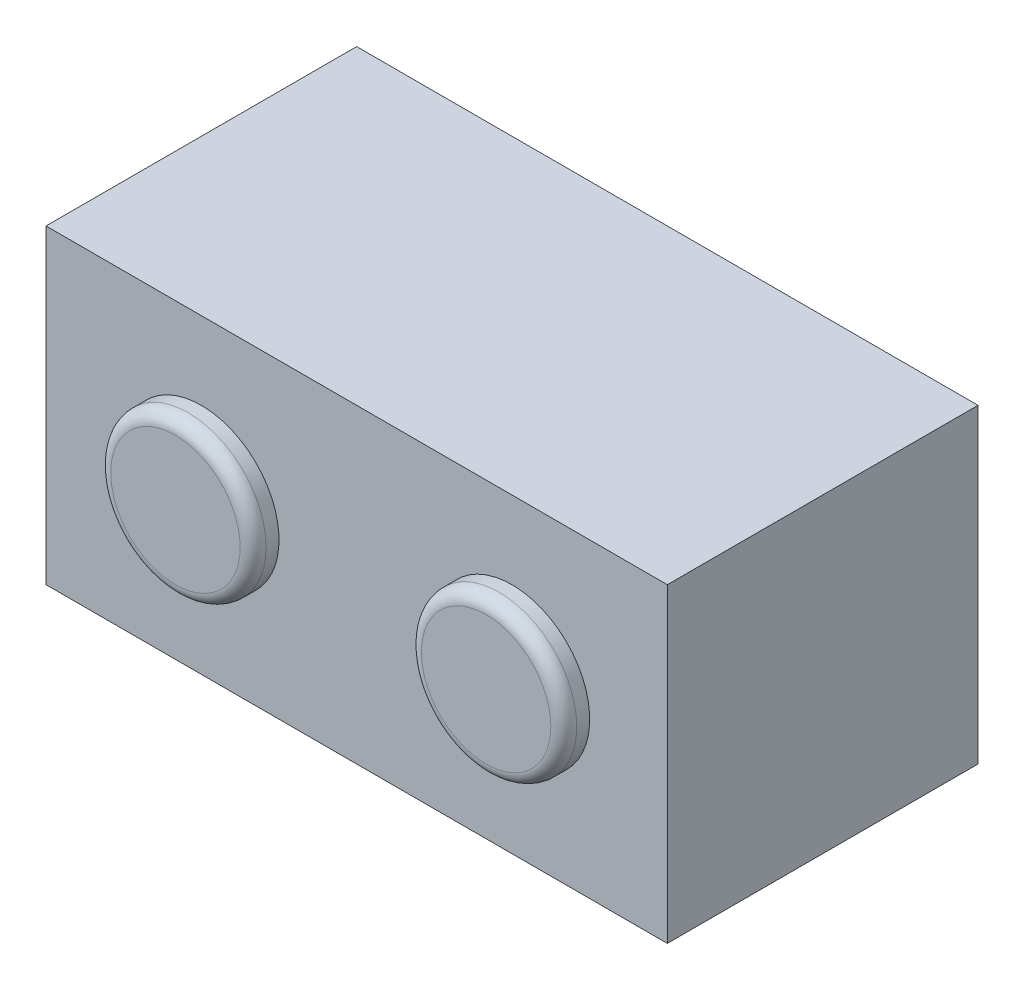
SolidWorks part; units mm, degrees
ref_plane "Front" through (0, 0, 0) normal (0, 0, 1) x (1, 0, 0)
ref_plane "Top" through (0, 0, 0) normal (0, 1, 0) x (1, 0, 0)
ref_plane "Right" through (0, 0, 0) normal (1, 0, 0) x (0, 0, -1)
sketch "Sketch1" plane through (0, 0, 0) normal (0, 1, 0) x (1, 0, 0)
  line L1 (-609.6, 304.8) -> (609.6, 304.8)
  line L2 (-609.6, 304.8) -> (-609.6, -304.8)
  line L3 (-609.6, -304.8) -> (609.6, -304.8)
  line L4 (609.6, 304.8) -> (609.6, -304.8)
  line L5 (-609.6, 304.8) -> (609.6, -304.8) construction
  line L6 (-609.6, -304.8) -> (609.6, 304.8) construction
  point P0 (0, 0)
  dimension "D1" = 1219.2
  dimension "D2" = 609.6
extrude "Boss-Extrude1" add sketch "Sketch1" along normal blind 609.6
sketch "Sketch2" plane through (0, 0, 304.8) normal (0, 0, 1) x (1, 0, 0)
  line L0 (0, 0) -> (0, 609.6) construction
  line L1 (-609.6, 0) -> (609.6, 0) construction
  line L2 (-609.6, 609.6) -> (609.6, 609.6) construction
  line L3 (0, 304.8) -> (-304.8, 304.8) construction
  line L4 (0, 304.8) -> (304.8, 304.8) construction
  circle A0 centre (-304.8, 304.8) radius 152.4
  circle A1 centre (304.8, 304.8) radius 152.4
  dimension "D1" = 304.8
  dimension "D2" = 304.8
extrude "Boss-Extrude2" add sketch "Sketch2" along normal blind 50.8
fillet "Fillet1" radius 25.4 2 edges at (457.2, 304.8, 355.6) (-152.4, 304.8, 355.6)
